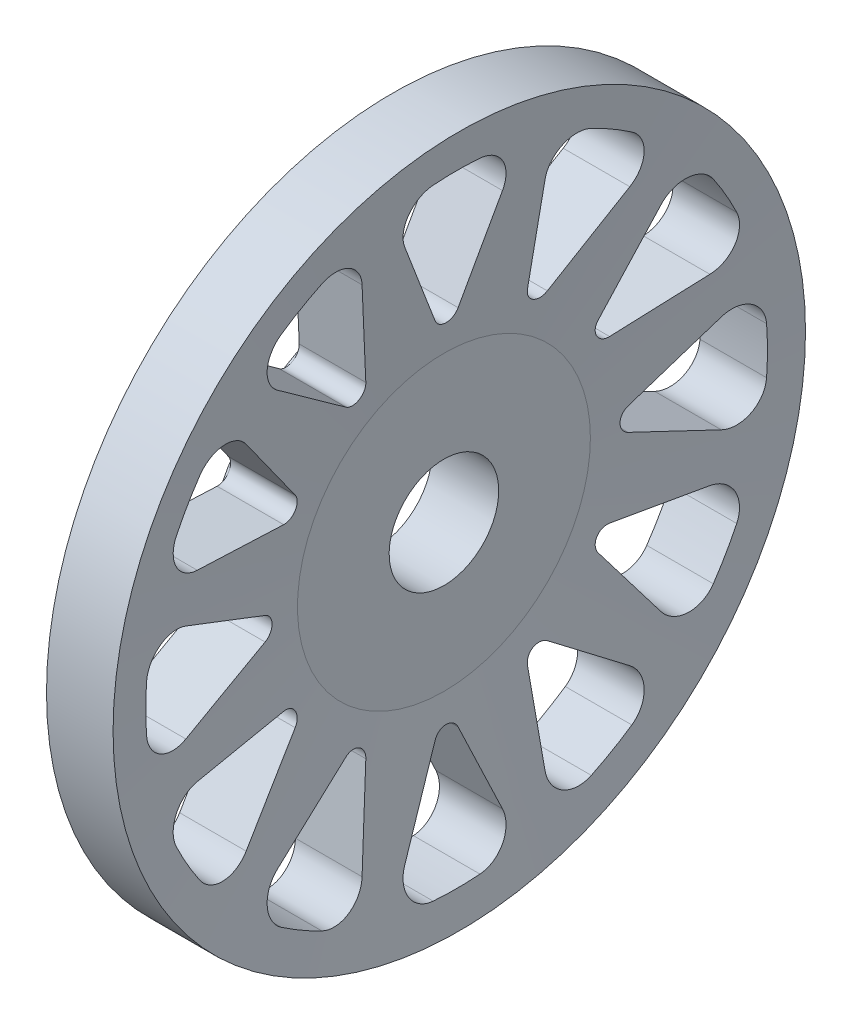
SolidWorks part; units mm, degrees
ref_plane "Front Plane" through (0, 0, 0) normal (0, 0, 1) x (1, 0, 0)
ref_plane "Top Plane" through (0, 0, 0) normal (0, 1, 0) x (1, 0, 0)
ref_plane "Right Plane" through (0, 0, 0) normal (1, 0, 0) x (0, 0, -1)
sketch "Sketch2" plane through (0, 0, 0) normal (0, 1, 0) x (1, 0, 0)
  line L0 (0, 0) -> (1.27, 16.51)
  line L1 (1.27, 16.51) -> (4.445, 16.51)
  line L2 (4.445, 16.51) -> (3.175, 0)
  line L3 (3.175, 0) -> (0, 0)
  line L4 (0, 0) -> (0, 16.51) construction
  dimension "D1" = 16.51
  dimension "D2" = 1.27
  dimension "D3" = 3.175
  dimension "D4" = 16.5588
revolve "Revolve1" add sketch "Sketch2" angle 360 about L3
sketch "Sketch3" plane through (0, 0, 0) normal (1, 0, 0) x (0, 0, -1)
  line L0 (-16.51, 0) -> (-16.51, -4.7654) construction
  line L1 (-26.0284, -0.7919) -> (-29.5209, -6.841) construction
  line L2 (-3.4925, 6.0492) -> (-6.985, 0)
  line L3 (-6.985, 0) -> (-3.4925, -6.0492)
  line L4 (-3.4925, -6.0492) -> (3.4925, -6.0492)
  line L5 (3.4925, -6.0492) -> (6.985, 0)
  line L6 (6.985, 0) -> (3.4925, 6.0492)
  line L7 (3.4925, 6.0492) -> (-3.4925, 6.0492)
  circle A0 centre (0, 0) radius 16.51 construction
  circle A1 centre (0, 0) radius 6.0492 construction
  dimension "D1" = 6.985
extrude "Cut-Extrude1" cut sketch "Sketch3" against normal through all both and the other way through all
ref_plane "Plane1" through (4.445, 0, 0) normal (1, 0, 0) x (0, 0, -1)
sketch "Sketch4" plane through (4.445, 0, 0) normal (1, 0, 0) x (0, 0, -1)
  line L0 (-3.4925, 6.0492) -> (3.4925, 6.0492) construction
  line L1 (3.4925, 6.0492) -> (6.985, 0) construction
  line L2 (6.985, 0) -> (3.4925, -6.0492) construction
  line L3 (3.4925, -6.0492) -> (-3.4925, -6.0492) construction
  line L4 (-3.4925, -6.0492) -> (-6.985, 0) construction
  line L5 (-6.985, 0) -> (-3.4925, 6.0492) construction
  line L6 (-3.4925, 6.0492) -> (3.4925, 6.0492) construction
  line L7 (3.4925, 6.0492) -> (6.985, 0) construction
  line L8 (6.985, 0) -> (3.4925, -6.0492) construction
  line L9 (3.4925, -6.0492) -> (-3.4925, -6.0492) construction
  line L10 (-3.4925, -6.0492) -> (-6.985, 0) construction
  line L11 (-6.985, 0) -> (-3.4925, 6.0492) construction
  line L12 (0, 8.255) -> (0, 14.8242) construction
  line L13 (0, 14.8242) -> (0, 11.5396) construction
  line L17 (0, 13.9947) -> (0, 11.5396) construction
  line L19 (0, 8.255) -> (0, 6.0492) construction
  line L20 (-2.3318, 12.7671) -> (-0.5475, 8.6569)
  line L21 (-2.3318, 12.7671) -> (0, 12.7671) construction
  line L22 (2.3318, 12.7671) -> (0.5475, 8.6569)
  line L23 (4.3642, 12.2225) -> (3.8543, 7.7709)
  line L24 (8.4029, 9.8908) -> (4.8026, 7.2233)
  line L25 (9.8908, 8.4029) -> (7.2233, 4.8026)
  line L26 (12.2225, 4.3642) -> (7.7709, 3.8543)
  line L27 (12.7671, 2.3318) -> (8.6569, 0.5475)
  line L28 (12.7671, -2.3318) -> (8.6569, -0.5475)
  line L29 (12.2225, -4.3642) -> (7.7709, -3.8543)
  line L30 (9.8908, -8.4029) -> (7.2233, -4.8026)
  line L31 (8.4029, -9.8908) -> (4.8026, -7.2233)
  line L32 (4.3642, -12.2225) -> (3.8543, -7.7709)
  line L33 (2.3318, -12.7671) -> (0.5475, -8.6569)
  line L34 (-2.3318, -12.7671) -> (-0.5475, -8.6569)
  line L35 (-4.3642, -12.2225) -> (-3.8543, -7.7709)
  line L36 (-8.4029, -9.8908) -> (-4.8026, -7.2233)
  line L37 (-9.8908, -8.4029) -> (-7.2233, -4.8026)
  line L38 (-12.2225, -4.3642) -> (-7.7709, -3.8543)
  line L39 (-12.7671, -2.3318) -> (-8.6569, -0.5475)
  line L40 (-12.7671, 2.3318) -> (-8.6569, 0.5475)
  line L41 (-12.2225, 4.3642) -> (-7.7709, 3.8543)
  line L42 (-9.8908, 8.4029) -> (-7.2233, 4.8026)
  line L43 (-8.4029, 9.8908) -> (-4.8026, 7.2233)
  line L44 (-4.3642, 12.2225) -> (-3.8543, 7.7709)
  circle A0 centre (0, 0) radius 16.5387 construction
  circle A1 centre (0, 0) radius 14.8242 construction
  circle A2 centre (0, 0) radius 8.255 construction
  arc A3 (-2.3318, 12.7671) -> (-1.1159, 14.7821) centre (-1.0072, 13.3421) cw
  arc A4 (2.3318, 12.7671) -> (1.1159, 14.7821) centre (1.0072, 13.3421) ccw
  arc A5 (-0.5475, 8.6569) -> (0.5475, 8.6569) centre (0, 8.8946) ccw
  arc A6 (-1.1159, 14.7821) -> (1.1159, 14.7821) centre (0, 0) cw
  arc A7 (6.4247, 13.3596) -> (8.3574, 12.2437) centre (0, 0) cw
  arc A8 (4.3642, 12.2225) -> (6.4247, 13.3596) centre (5.7988, 12.0582) cw
  arc A9 (8.4029, 9.8908) -> (8.3574, 12.2437) centre (7.5433, 11.0511) ccw
  arc A10 (3.8543, 7.7709) -> (4.8026, 7.2233) centre (4.4473, 7.7029) ccw
  arc A11 (12.2437, 8.3574) -> (13.3596, 6.4247) centre (0, 0) cw
  arc A12 (9.8908, 8.4029) -> (12.2437, 8.3574) centre (11.0511, 7.5433) cw
  arc A13 (12.2225, 4.3642) -> (13.3596, 6.4247) centre (12.0582, 5.7988) ccw
  arc A14 (7.2233, 4.8026) -> (7.7709, 3.8543) centre (7.7029, 4.4473) ccw
  arc A15 (14.7821, 1.1159) -> (14.7821, -1.1159) centre (0, 0) cw
  arc A16 (12.7671, 2.3318) -> (14.7821, 1.1159) centre (13.3421, 1.0072) cw
  arc A17 (12.7671, -2.3318) -> (14.7821, -1.1159) centre (13.3421, -1.0072) ccw
  arc A18 (8.6569, 0.5475) -> (8.6569, -0.5475) centre (8.8946, 0) ccw
  arc A19 (13.3596, -6.4247) -> (12.2437, -8.3574) centre (0, 0) cw
  arc A20 (12.2225, -4.3642) -> (13.3596, -6.4247) centre (12.0582, -5.7988) cw
  arc A21 (9.8908, -8.4029) -> (12.2437, -8.3574) centre (11.0511, -7.5433) ccw
  arc A22 (7.7709, -3.8543) -> (7.2233, -4.8026) centre (7.7029, -4.4473) ccw
  arc A23 (8.3574, -12.2437) -> (6.4247, -13.3596) centre (0, 0) cw
  arc A24 (8.4029, -9.8908) -> (8.3574, -12.2437) centre (7.5433, -11.0511) cw
  arc A25 (4.3642, -12.2225) -> (6.4247, -13.3596) centre (5.7988, -12.0582) ccw
  arc A26 (4.8026, -7.2233) -> (3.8543, -7.7709) centre (4.4473, -7.7029) ccw
  arc A27 (1.1159, -14.7821) -> (-1.1159, -14.7821) centre (0, 0) cw
  arc A28 (2.3318, -12.7671) -> (1.1159, -14.7821) centre (1.0072, -13.3421) cw
  arc A29 (-2.3318, -12.7671) -> (-1.1159, -14.7821) centre (-1.0072, -13.3421) ccw
  arc A30 (0.5475, -8.6569) -> (-0.5475, -8.6569) centre (0, -8.8946) ccw
  arc A31 (-6.4247, -13.3596) -> (-8.3574, -12.2437) centre (0, 0) cw
  arc A32 (-4.3642, -12.2225) -> (-6.4247, -13.3596) centre (-5.7988, -12.0582) cw
  arc A33 (-8.4029, -9.8908) -> (-8.3574, -12.2437) centre (-7.5433, -11.0511) ccw
  arc A34 (-3.8543, -7.7709) -> (-4.8026, -7.2233) centre (-4.4473, -7.7029) ccw
  arc A35 (-12.2437, -8.3574) -> (-13.3596, -6.4247) centre (0, 0) cw
  arc A36 (-9.8908, -8.4029) -> (-12.2437, -8.3574) centre (-11.0511, -7.5433) cw
  arc A37 (-12.2225, -4.3642) -> (-13.3596, -6.4247) centre (-12.0582, -5.7988) ccw
  arc A38 (-7.2233, -4.8026) -> (-7.7709, -3.8543) centre (-7.7029, -4.4473) ccw
  arc A39 (-14.7821, -1.1159) -> (-14.7821, 1.1159) centre (0, 0) cw
  arc A40 (-12.7671, -2.3318) -> (-14.7821, -1.1159) centre (-13.3421, -1.0072) cw
  arc A41 (-12.7671, 2.3318) -> (-14.7821, 1.1159) centre (-13.3421, 1.0072) ccw
  arc A42 (-8.6569, -0.5475) -> (-8.6569, 0.5475) centre (-8.8946, 0) ccw
  arc A43 (-13.3596, 6.4247) -> (-12.2437, 8.3574) centre (0, 0) cw
  arc A44 (-12.2225, 4.3642) -> (-13.3596, 6.4247) centre (-12.0582, 5.7988) cw
  arc A45 (-9.8908, 8.4029) -> (-12.2437, 8.3574) centre (-11.0511, 7.5433) ccw
  arc A46 (-7.7709, 3.8543) -> (-7.2233, 4.8026) centre (-7.7029, 4.4473) ccw
  arc A47 (-8.3574, 12.2437) -> (-6.4247, 13.3596) centre (0, 0) cw
  arc A48 (-8.4029, 9.8908) -> (-8.3574, 12.2437) centre (-7.5433, 11.0511) cw
  arc A49 (-4.3642, 12.2225) -> (-6.4247, 13.3596) centre (-5.7988, 12.0582) ccw
  arc A50 (-4.8026, 7.2233) -> (-3.8543, 7.7709) centre (-4.4473, 7.7029) ccw
  point P18 (0, 13.1819)
  point P26 (0, 12.7671)
  point P29 (0, 7.3956)
  point P132 (0, 0)
  dimension "D2" = 16.51
  dimension "D3" = 0.5969
  dimension "D4" = 12
  dimension "D1" = 1.7145
extrude "Cut-Extrude2" cut sketch "Sketch4" against normal through all both and the other way through all
ref_plane "Plane2" through (0, 16.51, 0) normal (0, 1, 0) x (1, 0, 0)
sketch "Sketch5" plane through (0, 16.51, 0) normal (0, 1, 0) x (1, 0, 0)
  line L0 (1.27, 0) -> (4.445, 0) construction
  line L1 (1.27, 16.51) -> (1.27, -16.51) construction
  line L2 (4.445, 16.51) -> (4.445, -16.51) construction
  circle A0 centre (2.8575, 0) radius 0.8255
  dimension "D1" = 1.651
ref_plane "Plane3" through (0, 0, 16.51) normal (0, 0, 1) x (1, 0, 0)
sketch "Sketch6" plane through (0, 0, 16.51) normal (0, 0, 1) x (1, 0, 0)
  line L0 (1.27, 0) -> (4.445, 0) construction
  line L1 (1.27, 16.51) -> (1.27, -16.51) construction
  line L2 (4.445, 16.51) -> (4.445, -16.51) construction
  circle A0 centre (2.8575, 0) radius 0.8255
  dimension "D1" = 1.651
ref_plane "Plane4" through (0, 0, -16.51) normal (0, 0, -1) x (-1, 0, 0)
sketch "Sketch7" plane through (0, 0, -16.51) normal (0, 0, -1) x (-1, 0, 0)
  line L0 (-4.445, 0) -> (-1.27, 0) construction
  line L1 (-4.445, 16.51) -> (-4.445, -16.51) construction
  line L2 (-1.27, 16.51) -> (-1.27, -16.51) construction
  circle A0 centre (-2.8575, 0) radius 0.8255
  dimension "D1" = 1.651
ref_plane "Plane5" through (0, -16.51, 0) normal (0, -1, 0) x (-1, 0, 0)
sketch "Sketch8" plane through (0, -16.51, 0) normal (0, -1, 0) x (-1, 0, 0)
  line L0 (-4.445, 0) -> (-1.27, 0) construction
  line L1 (-4.445, 16.51) -> (-4.445, -16.51) construction
  line L2 (-1.27, 16.51) -> (-1.27, -16.51) construction
  circle A0 centre (-2.8575, 0) radius 0.8255
  dimension "D1" = 1.651
ref_plane "Plane6" through (0, 8.255, 14.2981) normal (0, 0.5, 0.866) x (1, 0, 0)
sketch "Sketch9" plane through (0, 8.255, 14.2981) normal (0, 0.5, 0.866) x (1, 0, 0)
  line L0 (1.27, 0) -> (4.445, 0) construction
  line L1 (1.27, 16.51) -> (1.27, -16.51) construction
  line L2 (4.445, 16.51) -> (4.445, -16.51) construction
  circle A0 centre (2.8575, 0) radius 0.8255
  dimension "D1" = 1.651
ref_plane "Plane7" through (0, -8.255, -14.2981) normal (0, -0.5, -0.866) x (-1, 0, 0)
sketch "Sketch10" plane through (0, -8.255, -14.2981) normal (0, -0.5, -0.866) x (-1, 0, 0)
  line L0 (-4.445, 0) -> (-1.27, 0) construction
  line L1 (-4.445, 16.51) -> (-4.445, -16.51) construction
  line L2 (-1.27, 16.51) -> (-1.27, -16.51) construction
  circle A0 centre (-2.8575, 0) radius 0.8255
  dimension "D1" = 1.651
ref_plane "Plane8" through (0, 8.255, -14.2981) normal (0, 0.5, -0.866) x (-1, 0, 0)
sketch "Sketch11" plane through (0, 8.255, -14.2981) normal (0, 0.5, -0.866) x (-1, 0, 0)
  line L0 (-4.445, 0) -> (-1.27, 0) construction
  line L1 (-4.445, 16.51) -> (-4.445, -16.51) construction
  line L2 (-1.27, 16.51) -> (-1.27, -16.51) construction
  circle A0 centre (-2.8575, 0) radius 0.8255
  dimension "D1" = 1.651
ref_plane "Plane9" through (0, -8.255, 14.2981) normal (0, -0.5, 0.866) x (1, 0, 0)
sketch "Sketch12" plane through (0, -8.255, 14.2981) normal (0, -0.5, 0.866) x (1, 0, 0)
  line L0 (1.27, 0) -> (4.445, 0) construction
  line L1 (1.27, 16.51) -> (1.27, -16.51) construction
  line L2 (4.445, 16.51) -> (4.445, -16.51) construction
  circle A0 centre (2.8575, 0) radius 0.8255
  dimension "D1" = 1.651
ref_plane "Plane10" through (4.445, 0, 0) normal (1, 0, 0) x (0, 0, -1)
ref_plane "Plane11" through (0.5373, 0, 0) normal (1, 0, 0) x (0, 0, -1)
sketch "Sketch14" plane through (0.5373, 0, 0) normal (1, 0, 0) x (0, 0, -1)
  line L0 (-3.4925, 6.0492) -> (3.4925, 6.0492) construction
  line L1 (-6.985, 0) -> (-3.4925, 6.0492) construction
  line L2 (-3.4925, -6.0492) -> (-6.985, 0) construction
  line L3 (3.4925, -6.0492) -> (-3.4925, -6.0492) construction
  line L4 (6.985, 0) -> (3.4925, -6.0492) construction
  line L5 (3.4925, 6.0492) -> (6.985, 0) construction
  line L6 (-3.4925, 6.0492) -> (3.4925, 6.0492)
  line L7 (-6.985, 0) -> (-3.4925, 6.0492)
  line L8 (-3.4925, -6.0492) -> (-6.985, 0)
  line L9 (3.4925, -6.0492) -> (-3.4925, -6.0492)
  line L10 (6.985, 0) -> (3.4925, -6.0492)
  line L11 (3.4925, 6.0492) -> (6.985, 0)
  circle A0 centre (0, 0) radius 8.2977
  dimension "D1" = 16.5953
extrude "Boss-Extrude1" add sketch "Sketch14" along normal blind 1.27
sketch "Sketch15" plane through (0.5373, 0, 0) normal (-1, 0, 0) x (0, 0, 1)
  circle A0 centre (0, 0) radius 8.2977
extrude "Cut-Extrude11" cut sketch "Sketch15" along normal blind 1.27
sketch "Sketch16" plane through (0.5373, 0, 0) normal (-1, 0, 0) x (0, 0, 1)
  line L0 (-7.7709, 3.8543) -> (-12.2225, 4.3642) construction
  line L1 (-9.8908, 8.4029) -> (-7.2233, 4.8026) construction
  line L2 (-7.7709, 3.8543) -> (-12.2225, 4.3642)
  line L3 (-9.8908, 8.4029) -> (-7.2233, 4.8026)
  line L4 (-4.8026, 7.2233) -> (-8.4029, 9.8908)
  line L5 (-4.3642, 12.2225) -> (-3.8543, 7.7709)
  line L6 (-0.5475, 8.6569) -> (-2.3318, 12.7671)
  line L7 (2.3318, 12.7671) -> (0.5475, 8.6569)
  line L8 (3.8543, 7.7709) -> (4.3642, 12.2225)
  line L9 (8.4029, 9.8908) -> (4.8026, 7.2233)
  line L10 (7.2233, 4.8026) -> (9.8908, 8.4029)
  line L11 (12.2225, 4.3642) -> (7.7709, 3.8543)
  line L12 (8.6569, 0.5475) -> (12.7671, 2.3318)
  line L13 (12.7671, -2.3318) -> (8.6569, -0.5475)
  line L14 (7.7709, -3.8543) -> (12.2225, -4.3642)
  line L15 (9.8908, -8.4029) -> (7.2233, -4.8026)
  line L16 (4.8026, -7.2233) -> (8.4029, -9.8908)
  line L17 (4.3642, -12.2225) -> (3.8543, -7.7709)
  line L18 (0.5475, -8.6569) -> (2.3318, -12.7671)
  line L19 (-2.3318, -12.7671) -> (-0.5475, -8.6569)
  line L20 (-3.8543, -7.7709) -> (-4.3642, -12.2225)
  line L21 (-8.4029, -9.8908) -> (-4.8026, -7.2233)
  line L22 (-7.2233, -4.8026) -> (-9.8908, -8.4029)
  line L23 (-12.2225, -4.3642) -> (-7.7709, -3.8543)
  line L24 (-8.6569, -0.5475) -> (-12.7671, -2.3318)
  line L25 (-12.7671, 2.3318) -> (-8.6569, 0.5475)
  line L26 (-3.4925, 6.0492) -> (3.4925, 6.0492) construction
  line L27 (3.4925, 6.0492) -> (6.985, 0) construction
  line L28 (6.985, 0) -> (3.4925, -6.0492) construction
  line L29 (3.4925, -6.0492) -> (-3.4925, -6.0492) construction
  line L30 (-3.4925, -6.0492) -> (-6.985, 0) construction
  line L31 (-6.985, 0) -> (-3.4925, 6.0492) construction
  line L32 (-3.4925, 6.0492) -> (3.4925, 6.0492)
  line L33 (3.4925, 6.0492) -> (6.985, 0)
  line L34 (6.985, 0) -> (3.4925, -6.0492)
  line L35 (3.4925, -6.0492) -> (-3.4925, -6.0492)
  line L36 (-3.4925, -6.0492) -> (-6.985, 0)
  line L37 (-6.985, 0) -> (-3.4925, 6.0492)
  arc A0 (-9.8908, 8.4029) -> (-12.2437, 8.3574) centre (-11.0511, 7.5433) ccw construction
  arc A1 (-12.2437, 8.3574) -> (-13.3596, 6.4247) centre (0, 0) ccw construction
  arc A2 (-13.3596, 6.4247) -> (-12.2225, 4.3642) centre (-12.0582, 5.7988) ccw construction
  arc A3 (-7.7709, 3.8543) -> (-7.186, 4.1488) centre (-7.7029, 4.4473) ccw construction
  arc A4 (-7.186, 4.1488) -> (-7.2233, 4.8026) centre (-7.7029, 4.4473) ccw construction
  arc A5 (-9.8908, 8.4029) -> (-12.2437, 8.3574) centre (-11.0511, 7.5433) ccw
  arc A6 (-12.2437, 8.3574) -> (-13.3596, 6.4247) centre (0, 0) ccw
  arc A7 (-13.3596, 6.4247) -> (-12.2225, 4.3642) centre (-12.0582, 5.7988) ccw
  arc A8 (-7.7709, 3.8543) -> (-7.186, 4.1488) centre (-7.7029, 4.4473) ccw
  arc A9 (-7.186, 4.1488) -> (-7.2233, 4.8026) centre (-7.7029, 4.4473) ccw
  arc A10 (-4.3642, 12.2225) -> (-6.4247, 13.3596) centre (-5.7988, 12.0582) ccw
  arc A11 (-6.4247, 13.3596) -> (-8.3574, 12.2437) centre (0, 0) ccw
  arc A12 (-8.3574, 12.2437) -> (-8.4029, 9.8908) centre (-7.5433, 11.0511) ccw
  arc A13 (-4.8026, 7.2233) -> (-4.1488, 7.186) centre (-4.4473, 7.7029) ccw
  arc A14 (-4.1488, 7.186) -> (-3.8543, 7.7709) centre (-4.4473, 7.7029) ccw
  arc A15 (2.3318, 12.7671) -> (1.1159, 14.7821) centre (1.0072, 13.3421) ccw
  arc A16 (1.1159, 14.7821) -> (-1.1159, 14.7821) centre (0, 0) ccw
  arc A17 (-1.1159, 14.7821) -> (-2.3318, 12.7671) centre (-1.0072, 13.3421) ccw
  arc A18 (-0.5475, 8.6569) -> (0, 8.2977) centre (0, 8.8946) ccw
  arc A19 (0, 8.2977) -> (0.5475, 8.6569) centre (0, 8.8946) ccw
  arc A20 (8.4029, 9.8908) -> (8.3574, 12.2437) centre (7.5433, 11.0511) ccw
  arc A21 (8.3574, 12.2437) -> (6.4247, 13.3596) centre (0, 0) ccw
  arc A22 (6.4247, 13.3596) -> (4.3642, 12.2225) centre (5.7988, 12.0582) ccw
  arc A23 (3.8543, 7.7709) -> (4.1488, 7.186) centre (4.4473, 7.7029) ccw
  arc A24 (4.1488, 7.186) -> (4.8026, 7.2233) centre (4.4473, 7.7029) ccw
  arc A25 (12.2225, 4.3642) -> (13.3596, 6.4247) centre (12.0582, 5.7988) ccw
  arc A26 (13.3596, 6.4247) -> (12.2437, 8.3574) centre (0, 0) ccw
  arc A27 (12.2437, 8.3574) -> (9.8908, 8.4029) centre (11.0511, 7.5433) ccw
  arc A28 (7.2233, 4.8026) -> (7.186, 4.1488) centre (7.7029, 4.4473) ccw
  arc A29 (7.186, 4.1488) -> (7.7709, 3.8543) centre (7.7029, 4.4473) ccw
  arc A30 (12.7671, -2.3318) -> (14.7821, -1.1159) centre (13.3421, -1.0072) ccw
  arc A31 (14.7821, -1.1159) -> (14.7821, 1.1159) centre (0, 0) ccw
  arc A32 (14.7821, 1.1159) -> (12.7671, 2.3318) centre (13.3421, 1.0072) ccw
  arc A33 (8.6569, 0.5475) -> (8.2977, 0) centre (8.8946, 0) ccw
  arc A34 (8.2977, 0) -> (8.6569, -0.5475) centre (8.8946, 0) ccw
  arc A35 (9.8908, -8.4029) -> (12.2437, -8.3574) centre (11.0511, -7.5433) ccw
  arc A36 (12.2437, -8.3574) -> (13.3596, -6.4247) centre (0, 0) ccw
  arc A37 (13.3596, -6.4247) -> (12.2225, -4.3642) centre (12.0582, -5.7988) ccw
  arc A38 (7.7709, -3.8543) -> (7.186, -4.1488) centre (7.7029, -4.4473) ccw
  arc A39 (7.186, -4.1488) -> (7.2233, -4.8026) centre (7.7029, -4.4473) ccw
  arc A40 (4.3642, -12.2225) -> (6.4247, -13.3596) centre (5.7988, -12.0582) ccw
  arc A41 (6.4247, -13.3596) -> (8.3574, -12.2437) centre (0, 0) ccw
  arc A42 (8.3574, -12.2437) -> (8.4029, -9.8908) centre (7.5433, -11.0511) ccw
  arc A43 (4.8026, -7.2233) -> (4.1488, -7.186) centre (4.4473, -7.7029) ccw
  arc A44 (4.1488, -7.186) -> (3.8543, -7.7709) centre (4.4473, -7.7029) ccw
  arc A45 (-2.3318, -12.7671) -> (-1.1159, -14.7821) centre (-1.0072, -13.3421) ccw
  arc A46 (-1.1159, -14.7821) -> (1.1159, -14.7821) centre (0, 0) ccw
  arc A47 (1.1159, -14.7821) -> (2.3318, -12.7671) centre (1.0072, -13.3421) ccw
  arc A48 (0.5475, -8.6569) -> (0, -8.2977) centre (0, -8.8946) ccw
  arc A49 (0, -8.2977) -> (-0.5475, -8.6569) centre (0, -8.8946) ccw
  arc A50 (-8.4029, -9.8908) -> (-8.3574, -12.2437) centre (-7.5433, -11.0511) ccw
  arc A51 (-8.3574, -12.2437) -> (-6.4247, -13.3596) centre (0, 0) ccw
  arc A52 (-6.4247, -13.3596) -> (-4.3642, -12.2225) centre (-5.7988, -12.0582) ccw
  arc A53 (-3.8543, -7.7709) -> (-4.1488, -7.186) centre (-4.4473, -7.7029) ccw
  arc A54 (-4.1488, -7.186) -> (-4.8026, -7.2233) centre (-4.4473, -7.7029) ccw
  arc A55 (-12.2225, -4.3642) -> (-13.3596, -6.4247) centre (-12.0582, -5.7988) ccw
  arc A56 (-13.3596, -6.4247) -> (-12.2437, -8.3574) centre (0, 0) ccw
  arc A57 (-12.2437, -8.3574) -> (-9.8908, -8.4029) centre (-11.0511, -7.5433) ccw
  arc A58 (-7.2233, -4.8026) -> (-7.186, -4.1488) centre (-7.7029, -4.4473) ccw
  arc A59 (-7.186, -4.1488) -> (-7.7709, -3.8543) centre (-7.7029, -4.4473) ccw
  arc A60 (-12.7671, 2.3318) -> (-14.7821, 1.1159) centre (-13.3421, 1.0072) ccw
  arc A61 (-14.7821, 1.1159) -> (-14.7821, -1.1159) centre (0, 0) ccw
  arc A62 (-14.7821, -1.1159) -> (-12.7671, -2.3318) centre (-13.3421, -1.0072) ccw
  arc A63 (-8.6569, -0.5475) -> (-8.2977, 0) centre (-8.8946, 0) ccw
  arc A64 (-8.2977, 0) -> (-8.6569, 0.5475) centre (-8.8946, 0) ccw
  circle A65 centre (0, 0) radius 16.51 construction
  circle A66 centre (0, 0) radius 16.51 construction
  point P123 (0, 0)
  dimension "D1" = 12
sketch "Sketch17" plane through (0.5373, 0, 0) normal (-1, 0, 0) x (0, 0, 1)
  circle A0 centre (-24.7396, 9.2392) radius 2.6125 construction
  circle A1 centre (0, 0) radius 2.6125
  circle A2 centre (0, 0) radius 7.5657
  dimension "D1" = 5.225
extrude "Boss-Extrude2" add sketch "Sketch17" against normal up to vertex (3.175 mm away)
sketch "Sketch18" plane through (3.7123, 0, 0) normal (1, 0, 0) x (0, 0, -1)
  line L0 (-9.8908, 8.4029) -> (-7.2233, 4.8026) construction
  line L1 (-7.7709, 3.8543) -> (-12.2225, 4.3642) construction
  line L2 (-9.8908, 8.4029) -> (-7.2233, 4.8026) construction
  line L3 (-7.7709, 3.8543) -> (-12.2225, 4.3642) construction
  line L4 (-10.0438, 8.2895) -> (-7.3764, 4.6892)
  line L5 (-7.7492, 4.0435) -> (-12.2009, 4.5534)
  line L6 (-4.5534, 12.2009) -> (-4.0435, 7.7492)
  line L7 (-4.6892, 7.3764) -> (-8.2895, 10.0438)
  line L8 (2.157, 12.843) -> (0.3728, 8.7327)
  line L9 (-0.3728, 8.7327) -> (-2.157, 12.843)
  line L10 (8.2895, 10.0438) -> (4.6892, 7.3764)
  line L11 (4.0435, 7.7492) -> (4.5534, 12.2009)
  line L12 (12.2009, 4.5534) -> (7.7492, 4.0435)
  line L13 (7.3764, 4.6892) -> (10.0438, 8.2895)
  line L14 (12.843, -2.157) -> (8.7327, -0.3728)
  line L15 (8.7327, 0.3728) -> (12.843, 2.157)
  line L16 (10.0438, -8.2895) -> (7.3764, -4.6892)
  line L17 (7.7492, -4.0435) -> (12.2009, -4.5534)
  line L18 (4.5534, -12.2009) -> (4.0435, -7.7492)
  line L19 (4.6892, -7.3764) -> (8.2895, -10.0438)
  line L20 (-2.157, -12.843) -> (-0.3728, -8.7327)
  line L21 (0.3728, -8.7327) -> (2.157, -12.843)
  line L22 (-8.2895, -10.0438) -> (-4.6892, -7.3764)
  line L23 (-4.0435, -7.7492) -> (-4.5534, -12.2009)
  line L24 (-12.2009, -4.5534) -> (-7.7492, -4.0435)
  line L25 (-7.3764, -4.6892) -> (-10.0438, -8.2895)
  line L26 (-12.843, 2.157) -> (-8.7327, 0.3728)
  line L27 (-8.7327, -0.3728) -> (-12.843, -2.157)
  circle A0 centre (0, 0) radius 6.985
  circle A1 centre (0, 0) radius 2.6125
  circle A2 centre (0, 0) radius 16.51
  circle A3 centre (0, 0) radius 19.05
  arc A4 (-7.7709, 3.8543) -> (-7.2233, 4.8026) centre (-7.7029, 4.4473) ccw construction
  arc A5 (-9.8908, 8.4029) -> (-12.2437, 8.3574) centre (-11.0511, 7.5433) ccw construction
  arc A6 (-12.2437, 8.3574) -> (-13.3596, 6.4247) centre (0, 0) ccw construction
  arc A7 (-13.3596, 6.4247) -> (-12.2225, 4.3642) centre (-12.0582, 5.7988) ccw construction
  arc A8 (-7.7709, 3.8543) -> (-7.2233, 4.8026) centre (-7.7029, 4.4473) ccw construction
  arc A9 (-9.8908, 8.4029) -> (-12.2437, 8.3574) centre (-11.0511, 7.5433) ccw construction
  arc A10 (-12.2437, 8.3574) -> (-13.3596, 6.4247) centre (0, 0) ccw construction
  arc A11 (-13.3596, 6.4247) -> (-12.2225, 4.3642) centre (-12.0582, 5.7988) ccw construction
  arc A12 (-7.7492, 4.0435) -> (-7.3764, 4.6892) centre (-7.7029, 4.4473) ccw
  arc A13 (-10.0438, 8.2895) -> (-12.0864, 8.25) centre (-11.0511, 7.5433) ccw
  arc A14 (-12.0864, 8.25) -> (-13.1879, 6.3421) centre (0, 0) ccw
  arc A15 (-13.1879, 6.3421) -> (-12.2009, 4.5534) centre (-12.0582, 5.7988) ccw
  arc A16 (-4.6892, 7.3764) -> (-4.0435, 7.7492) centre (-4.4473, 7.7029) ccw
  arc A17 (-4.5534, 12.2009) -> (-6.3421, 13.1879) centre (-5.7988, 12.0582) ccw
  arc A18 (-6.3421, 13.1879) -> (-8.25, 12.0864) centre (0, 0) ccw
  arc A19 (-8.25, 12.0864) -> (-8.2895, 10.0438) centre (-7.5433, 11.0511) ccw
  arc A20 (-0.3728, 8.7327) -> (0.3728, 8.7327) centre (0, 8.8946) ccw
  arc A21 (2.157, 12.843) -> (1.1015, 14.5921) centre (1.0072, 13.3421) ccw
  arc A22 (1.1015, 14.5921) -> (-1.1015, 14.5921) centre (0, 0) ccw
  arc A23 (-1.1015, 14.5921) -> (-2.157, 12.843) centre (-1.0072, 13.3421) ccw
  arc A24 (4.0435, 7.7492) -> (4.6892, 7.3764) centre (4.4473, 7.7029) ccw
  arc A25 (8.2895, 10.0438) -> (8.25, 12.0864) centre (7.5433, 11.0511) ccw
  arc A26 (8.25, 12.0864) -> (6.3421, 13.1879) centre (0, 0) ccw
  arc A27 (6.3421, 13.1879) -> (4.5534, 12.2009) centre (5.7988, 12.0582) ccw
  arc A28 (7.3764, 4.6892) -> (7.7492, 4.0435) centre (7.7029, 4.4473) ccw
  arc A29 (12.2009, 4.5534) -> (13.1879, 6.3421) centre (12.0582, 5.7988) ccw
  arc A30 (13.1879, 6.3421) -> (12.0864, 8.25) centre (0, 0) ccw
  arc A31 (12.0864, 8.25) -> (10.0438, 8.2895) centre (11.0511, 7.5433) ccw
  arc A32 (8.7327, 0.3728) -> (8.7327, -0.3728) centre (8.8946, 0) ccw
  arc A33 (12.843, -2.157) -> (14.5921, -1.1015) centre (13.3421, -1.0072) ccw
  arc A34 (14.5921, -1.1015) -> (14.5921, 1.1015) centre (0, 0) ccw
  arc A35 (14.5921, 1.1015) -> (12.843, 2.157) centre (13.3421, 1.0072) ccw
  arc A36 (7.7492, -4.0435) -> (7.3764, -4.6892) centre (7.7029, -4.4473) ccw
  arc A37 (10.0438, -8.2895) -> (12.0864, -8.25) centre (11.0511, -7.5433) ccw
  arc A38 (12.0864, -8.25) -> (13.1879, -6.3421) centre (0, 0) ccw
  arc A39 (13.1879, -6.3421) -> (12.2009, -4.5534) centre (12.0582, -5.7988) ccw
  arc A40 (4.6892, -7.3764) -> (4.0435, -7.7492) centre (4.4473, -7.7029) ccw
  arc A41 (4.5534, -12.2009) -> (6.3421, -13.1879) centre (5.7988, -12.0582) ccw
  arc A42 (6.3421, -13.1879) -> (8.25, -12.0864) centre (0, 0) ccw
  arc A43 (8.25, -12.0864) -> (8.2895, -10.0438) centre (7.5433, -11.0511) ccw
  arc A44 (0.3728, -8.7327) -> (-0.3728, -8.7327) centre (0, -8.8946) ccw
  arc A45 (-2.157, -12.843) -> (-1.1015, -14.5921) centre (-1.0072, -13.3421) ccw
  arc A46 (-1.1015, -14.5921) -> (1.1015, -14.5921) centre (0, 0) ccw
  arc A47 (1.1015, -14.5921) -> (2.157, -12.843) centre (1.0072, -13.3421) ccw
  arc A48 (-4.0435, -7.7492) -> (-4.6892, -7.3764) centre (-4.4473, -7.7029) ccw
  arc A49 (-8.2895, -10.0438) -> (-8.25, -12.0864) centre (-7.5433, -11.0511) ccw
  arc A50 (-8.25, -12.0864) -> (-6.3421, -13.1879) centre (0, 0) ccw
  arc A51 (-6.3421, -13.1879) -> (-4.5534, -12.2009) centre (-5.7988, -12.0582) ccw
  arc A52 (-7.3764, -4.6892) -> (-7.7492, -4.0435) centre (-7.7029, -4.4473) ccw
  arc A53 (-12.2009, -4.5534) -> (-13.1879, -6.3421) centre (-12.0582, -5.7988) ccw
  arc A54 (-13.1879, -6.3421) -> (-12.0864, -8.25) centre (0, 0) ccw
  arc A55 (-12.0864, -8.25) -> (-10.0438, -8.2895) centre (-11.0511, -7.5433) ccw
  arc A56 (-8.7327, -0.3728) -> (-8.7327, 0.3728) centre (-8.8946, 0) ccw
  arc A57 (-12.843, 2.157) -> (-14.5921, 1.1015) centre (-13.3421, 1.0072) ccw
  arc A58 (-14.5921, 1.1015) -> (-14.5921, -1.1015) centre (0, 0) ccw
  arc A59 (-14.5921, -1.1015) -> (-12.843, -2.157) centre (-13.3421, -1.0072) ccw
  point P125 (0, 0)
  dimension "D1" = 2.54
  dimension "D2" = 33.02
  dimension "D3" = 13.97
  dimension "D4" = 5.225
  dimension "D5" = 0.1905
  dimension "D6" = 12
